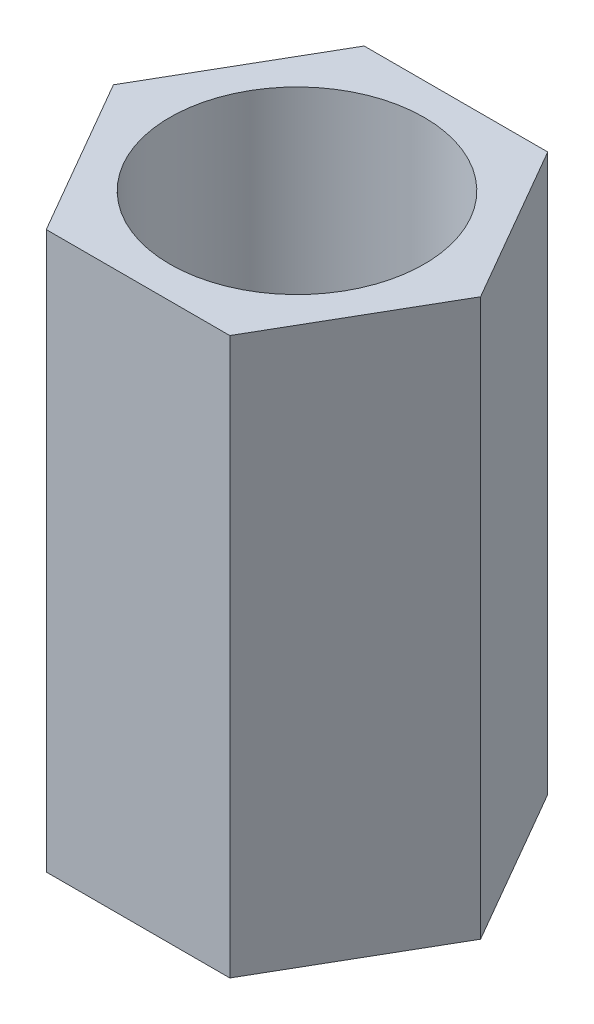
SolidWorks part; units mm, degrees
ref_plane "정면" through (0, 0, 0) normal (0, 0, 1) x (1, 0, 0)
ref_plane "윗면" through (0, 0, 0) normal (0, 1, 0) x (1, 0, 0)
ref_plane "우측면" through (0, 0, 0) normal (1, 0, 0) x (0, 0, -1)
sketch "스케치1" plane through (0, 0, 0) normal (0, 1, 0) x (1, 0, 0)
  line L1 (2.3094, 0) -> (1.1547, 2)
  line L2 (1.1547, 2) -> (-1.1547, 2)
  line L3 (-1.1547, 2) -> (-2.3094, 0)
  line L4 (-2.3094, 0) -> (-1.1547, -2)
  line L5 (-1.1547, -2) -> (1.1547, -2)
  line L6 (1.1547, -2) -> (2.3094, 0)
  circle A0 centre (0, 0) radius 1.6
  circle A1 centre (0, 0) radius 2 construction
extrude "보스-돌출2" add sketch "스케치1" along normal blind 7
